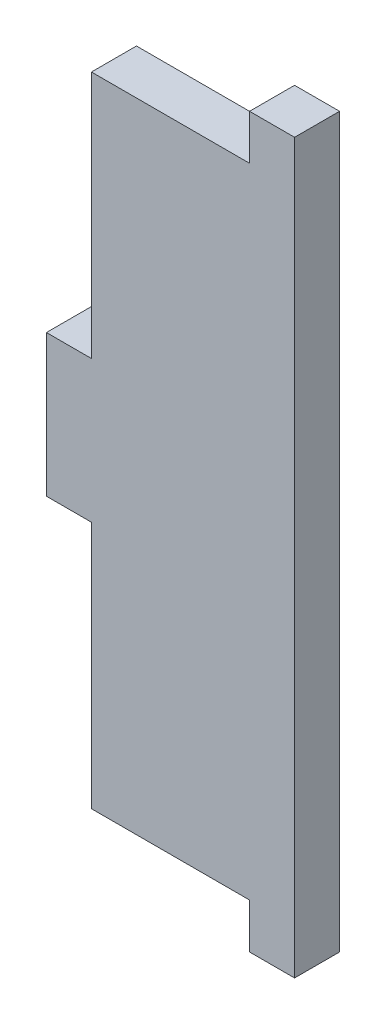
SolidWorks part; units mm, degrees
ref_plane "Front Plane" through (0, 0, 0) normal (0, 0, 1) x (1, 0, 0)
ref_plane "Top Plane" through (0, 0, 0) normal (0, 1, 0) x (1, 0, 0)
ref_plane "Right Plane" through (0, 0, 0) normal (1, 0, 0) x (0, 0, -1)
sketch "Sketch1" plane through (0, 0, 0) normal (0, 0, 1) x (1, 0, 0)
  line L0 (0, 0) -> (0, -35)
  line L1 (0, -35) -> (-6.35, -35)
  line L2 (-6.35, -35) -> (-6.35, -55)
  line L3 (-6.35, -55) -> (0, -55)
  line L4 (0, -55) -> (0, -90)
  line L6 (28.65, -90) -> (28.65, -6.35)
  line L8 (28.65, -90) -> (28.65, -96.35)
  line L9 (28.65, -96.35) -> (22.3, -96.35)
  line L10 (22.3, -96.35) -> (22.3, -90)
  line L12 (0, 0) -> (22.3, 0)
  line L14 (28.65, -6.35) -> (28.65, 6.35)
  line L15 (28.65, 6.35) -> (22.3, 6.35)
  line L16 (22.3, 0) -> (22.3, 6.35)
  line L17 (0, -90) -> (22.3, -90)
  dimension "D1" = 90
  dimension "D2" = 102.7
  dimension "D3" = 20
  dimension "D4" = 35
  dimension "D5" = 6.35
  dimension "D6" = 6.35
  dimension "D7" = 6.35
  dimension "D8" = 6.35
  dimension "D9" = 6.35
  dimension "D10" = 41.35
extrude "Boss-Extrude1" add sketch "Sketch1" along normal blind 6.35
